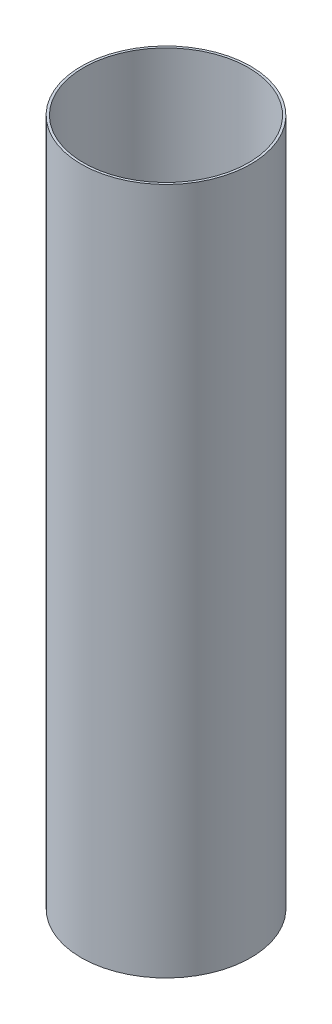
SolidWorks part; units mm, degrees
material "C-Glass Fiber"
ref_plane "Front Plane" through (0, 0, 0) normal (0, 0, 1) x (1, 0, 0)
ref_plane "Top Plane" through (0, 0, 0) normal (0, 1, 0) x (1, 0, 0)
ref_plane "Right Plane" through (0, 0, 0) normal (1, 0, 0) x (0, 0, -1)
sketch "Sketch1" plane through (0, 0, 0) normal (0, 1, 0) x (1, 0, 0)
  circle A0 centre (0, 0) radius 78.359
  circle A1 centre (0, 0) radius 76.2
  dimension "D1" = 152.4
  dimension "D2" = 156.718
extrude "Boss-Extrude1" add sketch "Sketch1" along normal blind 635
